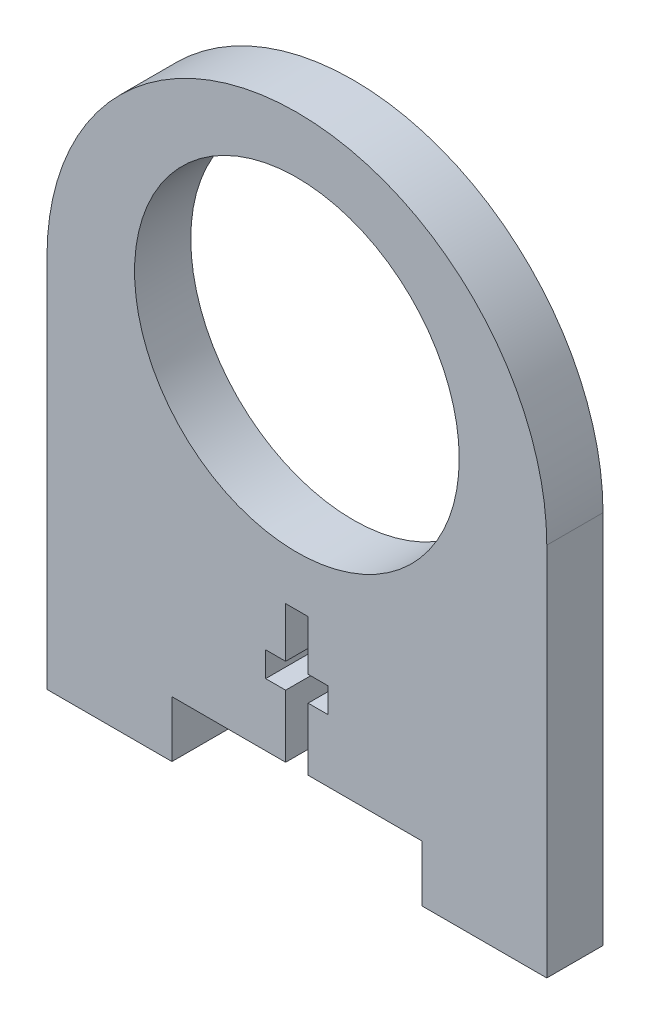
SolidWorks part; units mm, degrees
ref_plane "Front Plane" through (0, 0, 0) normal (0, 0, 1) x (1, 0, 0)
ref_plane "Top Plane" through (0, 0, 0) normal (0, 1, 0) x (1, 0, 0)
ref_plane "Right Plane" through (0, 0, 0) normal (1, 0, 0) x (0, 0, -1)
sketch "Sketch1" plane through (0, 0, 0) normal (0, 0, 1) x (1, 0, 0)
  line L0 (-25.4, 22.2148) -> (25.4, 22.2148) construction
  line L1 (25.4, -19.05) -> (-25.4, -19.05)
  line L2 (25.4, -19.05) -> (25.4, 19.05)
  line L3 (25.4, 19.05) -> (-25.4, 19.05) construction
  line L4 (-25.4, -19.05) -> (-25.4, 19.05)
  line L5 (25.4, -19.05) -> (-25.4, 19.05) construction
  line L6 (25.4, 19.05) -> (-25.4, -19.05) construction
  line L7 (0, 44.45) -> (0, -19.05) construction
  arc A0 (-25.4, 19.05) -> (25.4, 19.05) centre (0, 19.05) cw
  circle A3 centre (0, 22.2148) radius 16.5 construction
  circle A4 centre (0, 31.2148) radius 2.5 construction
  point P0 (0, 0)
  dimension "D2" = 33
  dimension "D4" = 5
  dimension "D1" = 41.2648
  dimension "D3" = 9
  dimension "D5" = 50.8
  dimension "D6" = 38.1
extrude "Boss-Extrude1" add sketch "Sketch1" along normal blind 5.715
sketch "Sketch2" plane through (0, 0, 5.715) normal (0, 0, 1) x (1, 0, 0)
  circle A0 centre (0, 22.2148) radius 16.5
  dimension "D1" = 33
extrude "Cut-Extrude1" cut sketch "Sketch2" against normal up to next
sketch "Sketch3" plane through (0, 0, 5.715) normal (0, 0, 1) x (1, 0, 0)
  line L0 (25.4, -19.05) -> (-25.4, -19.05) construction
  line L1 (-12.7, -19.05) -> (12.7, -19.05)
  line L2 (-12.7, -19.05) -> (-12.7, -13.335)
  line L3 (-12.7, -13.335) -> (12.7, -13.335)
  line L4 (12.7, -19.05) -> (12.7, -13.335)
  line L6 (0, 44.45) -> (0, -19.05) construction
  point P6 (0, -13.335)
  dimension "D1" = 5.715
  dimension "D2" = 25.4
extrude "Cut-Extrude2" cut sketch "Sketch3" against normal up to next
sketch "Sketch4" plane through (0, 0, 5.715) normal (0, 0, 1) x (1, 0, 0)
  line L0 (-25.4, -19.05) -> (-12.7, -19.05) construction
  line L1 (25.4, -19.05) -> (-25.4, -19.05) construction
  line L2 (-12.7, -13.335) -> (-12.7, -19.05) construction
  line L3 (-20.2866, -1014.3325) -> (-20.2866, 48985.6675) construction
  line L4 (0, -34.925) -> (0, 34.925) construction
  line L5 (-17.4291, -3.81) -> (-23.1441, -3.81)
  line L6 (-17.4291, -3.81) -> (-17.4291, 2.54)
  line L7 (-17.4291, 2.54) -> (-23.1441, 2.54)
  line L8 (-23.1441, -3.81) -> (-23.1441, 2.54)
  line L9 (-17.4291, -3.81) -> (-23.1441, 2.54) construction
  line L10 (-17.4291, 2.54) -> (-23.1441, -3.81) construction
  line L11 (17.4291, -6.35) -> (23.1441, -12.7) construction
  line L12 (-17.4291, -12.7) -> (-23.1441, -12.7)
  line L13 (-17.4291, -12.7) -> (-17.4291, -6.35)
  line L14 (-17.4291, -6.35) -> (-23.1441, -6.35)
  line L15 (-23.1441, -12.7) -> (-23.1441, -6.35)
  line L16 (-17.4291, -12.7) -> (-23.1441, -6.35) construction
  line L17 (-17.4291, -6.35) -> (-23.1441, -12.7) construction
  line L18 (17.4291, -12.7) -> (23.1441, -6.35) construction
  line L19 (17.4291, 2.54) -> (23.1441, -3.81) construction
  line L20 (17.4291, -3.81) -> (23.1441, 2.54) construction
  line L21 (23.1441, -12.7) -> (23.1441, -6.35)
  line L22 (17.4291, -6.35) -> (23.1441, -6.35)
  line L23 (17.4291, -12.7) -> (17.4291, -6.35)
  line L24 (17.4291, -12.7) -> (23.1441, -12.7)
  line L25 (23.1441, -3.81) -> (23.1441, 2.54)
  line L26 (17.4291, 2.54) -> (23.1441, 2.54)
  line L27 (17.4291, -3.81) -> (17.4291, 2.54)
  line L28 (17.4291, -3.81) -> (23.1441, -3.81)
  point P7 (-20.2866, -19.05)
  point P9 (-20.2866, -0.635)
  point P17 (-20.2866, -9.525)
  point P23 (-19.05, -19.05)
  point P35 (20.2866, -9.525)
  point P36 (20.2866, -0.635)
  dimension "D1" = 6.35
  dimension "D2" = 6.35
  dimension "D3" = 5.715
  dimension "D4" = 5.715
  dimension "D5" = 6.35
  dimension "D6" = 2.54
  dimension "D7" = 1.2366
extrude "Cut-Extrude3" [suppressed] cut sketch "Sketch4" against normal up to next
sketch "Sketch5" plane through (0, 0, 5.715) normal (0, 0, 1) x (1, 0, 0)
  line L0 (0, 44.45) -> (0, -19.05) construction
  line L1 (3.175, -6.985) -> (1.143, -6.985)
  line L2 (3.175, -6.985) -> (3.175, -4.445)
  line L3 (3.175, -4.445) -> (1.143, -4.445)
  line L4 (-3.175, -6.985) -> (-3.175, -4.445)
  line L5 (3.175, -6.985) -> (-3.175, -4.445) construction
  line L6 (3.175, -4.445) -> (-3.175, -6.985) construction
  line L7 (12.7, -13.335) -> (-12.7, -13.335) construction
  line L8 (-1.143, -4.445) -> (-3.175, -4.445)
  line L9 (-1.143, -13.335) -> (1.143, -13.335)
  line L10 (-1.143, -13.335) -> (-1.143, -6.985)
  line L11 (-1.143, 0.635) -> (1.143, 0.635)
  line L12 (1.143, -13.335) -> (1.143, -6.985)
  line L13 (-1.143, -4.445) -> (-1.143, 0.635)
  line L14 (1.143, -4.445) -> (1.143, 0.635)
  line L15 (-1.143, -6.985) -> (-3.175, -6.985)
  point P0 (0, -5.715)
  point P14 (0, 0.635)
  dimension "D1" = 6.35
  dimension "D2" = 2.54
  dimension "D3" = 6.35
  dimension "D4" = 2.286
  dimension "D5" = 13.97
extrude "Cut-Extrude4" cut sketch "Sketch5" against normal up to next
equation "\"D2@Sketch1\"=33mm"
equation "\"D1@Sketch1\"=0.75+0.6496+\"t\""
equation "\"t\"= 0.225"
equation "\"D1@Boss-Extrude1\"=\"t\""
equation "\"D1@Sketch3\"=\"t\""
equation "\"D4@Sketch4\"=\"t\""
equation "\"D3@Sketch4\"=\"t\""
